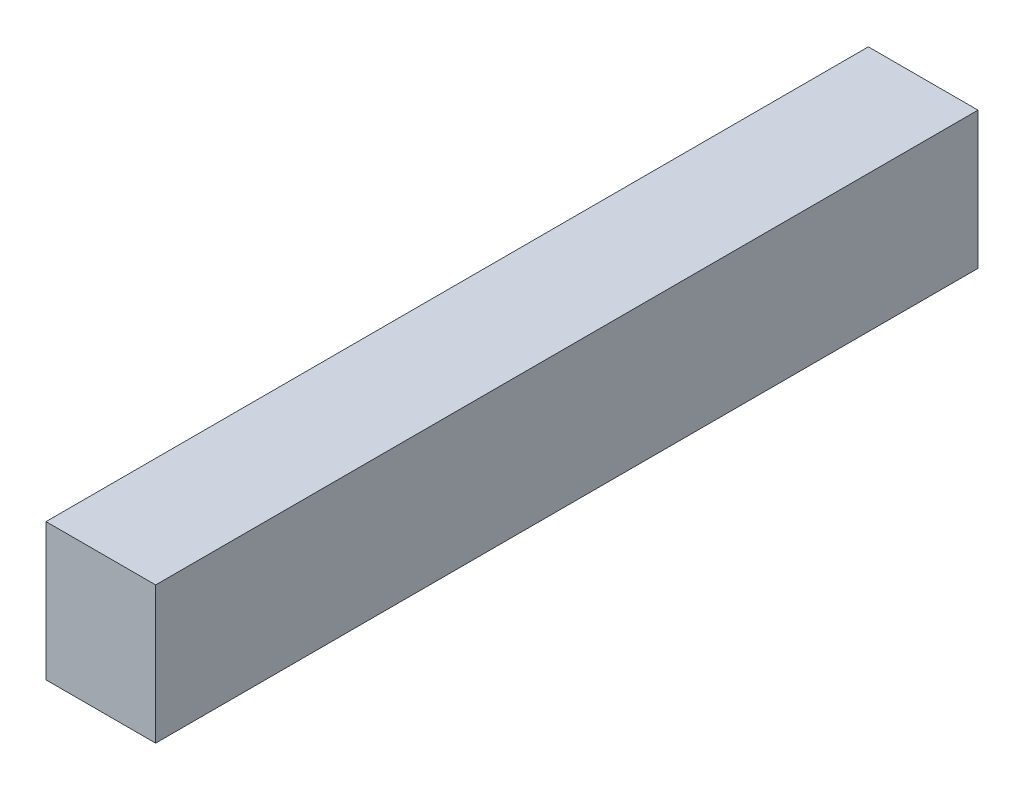
SolidWorks part; units mm, degrees
material "AISI 1015 Aço, trefilado (SS)"
ref_plane "Plano frontal" through (0, 0, 0) normal (0, 0, 1) x (1, 0, 0)
ref_plane "Plano superior" through (0, 0, 0) normal (0, 1, 0) x (1, 0, 0)
ref_plane "Plano direito" through (0, 0, 0) normal (1, 0, 0) x (0, 0, -1)
sketch "Esboço1" plane through (0, 0, 0) normal (0, 0, 1) x (1, 0, 0)
  line L1 (0, 0) -> (4, 0)
  line L2 (0, 0) -> (0, 5)
  line L3 (0, 5) -> (4, 5)
  line L4 (4, 0) -> (4, 5)
  dimension "D1" = 5
  dimension "D2" = 4
extrude "Ressalto-extrusão1" add sketch "Esboço1" along normal blind 30
